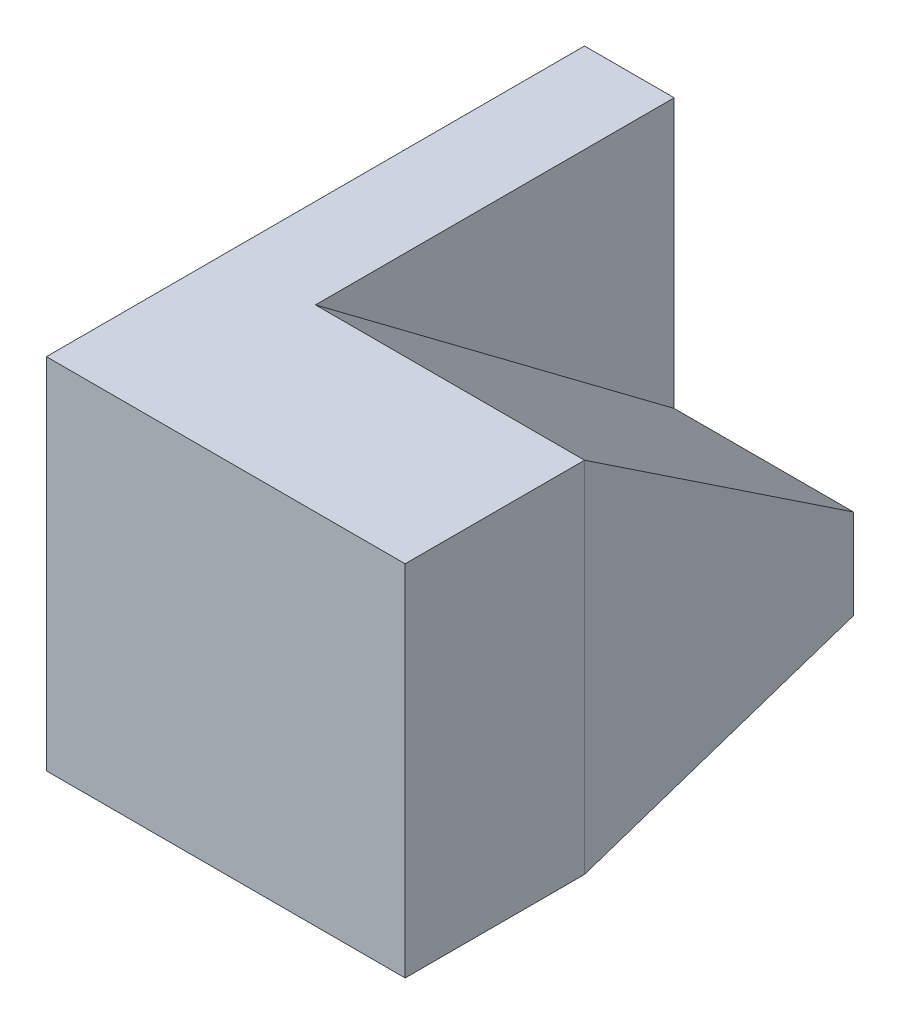
SolidWorks part; units mm, degrees
ref_plane "前基準面" through (0, 0, 0) normal (0, 0, 1) x (1, 0, 0)
ref_plane "上基準面" through (0, 0, 0) normal (0, 1, 0) x (1, 0, 0)
ref_plane "右基準面" through (0, 0, 0) normal (1, 0, 0) x (0, 0, -1)
sketch "草圖2" plane through (0, 0, 0) normal (1, 0, 0) x (0, 0, -1)
  line L1 (0, 0) -> (-60, 0)
  line L2 (0, 0) -> (0, -40)
  line L3 (0, -40) -> (-60, -40)
  line L4 (-60, 0) -> (-60, -40)
  dimension "D1" = 40
  dimension "D2" = 60
extrude "填料-伸長1" add sketch "草圖2" along normal blind 40
sketch "草圖3" plane through (0, 0, 0) normal (0, 1, 0) x (1, 0, 0)
  line L0 (30, 0) -> (40, -40)
  line L1 (40, 0) -> (0, 0) construction
  line L2 (40, 0) -> (40, -60) construction
  line L3 (40, -40) -> (40, 0)
  line L4 (40, 0) -> (30, 0)
  dimension "D1" = 40
  dimension "D2" = 10
extrude "除料-伸長1" cut sketch "草圖3" against normal blind 40
sketch "草圖5" plane through (0, 0, 0) normal (0, 1, 0) x (1, 0, 0)
  line L0 (30, 0) -> (10, 0)
  line L1 (30, 0) -> (0, 0) construction
  line L2 (10, 0) -> (10, -40)
  line L3 (40, -40) -> (10, -40)
  line L4 (0, 0) -> (0, -60) construction
  line L5 (40, -40) -> (30, 0)
  dimension "D1" = 10
sketch "草圖6" plane through (28.2353, 0, -7.0588) normal (0.9701, 0, -0.2425) x (-0.2425, 0, -0.9701)
  line L0 (-48.5071, 0) -> (-7.2761, -30)
  line L1 (-7.2761, -40) -> (-7.2761, 0) construction
  dimension "D1" = 10
sweep "除料-掃出1" cut profiles "草圖5" path "草圖6"
sketch "草圖7" plane through (0, 0, 0) normal (0, 1, 0) x (1, 0, 0)
  line L0 (10, -40) -> (10, 0)
  line L1 (10, 0) -> (0, 0)
  line L2 (0, 0) -> (0, -40)
  line L3 (0, 0) -> (0, -60) construction
  line L4 (0, -40) -> (10, -40)
extrude "填料-伸長2" add sketch "草圖7" against normal up to surface (30 mm away)
